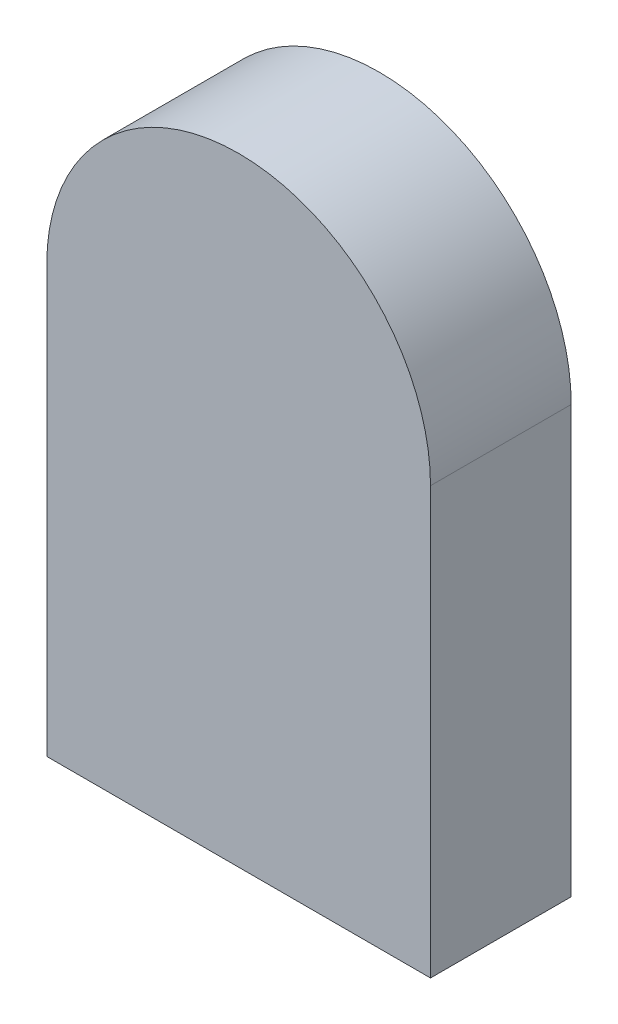
SolidWorks part; units mm, degrees
ref_plane "Front Plane" through (0, 0, 0) normal (0, 0, 1) x (1, 0, 0)
ref_plane "Top Plane" through (0, 0, 0) normal (0, 1, 0) x (1, 0, 0)
ref_plane "Right Plane" through (0, 0, 0) normal (1, 0, 0) x (0, 0, -1)
sketch "Sketch1" plane through (0, 0, 0) normal (0, 0, 1) x (1, 0, 0)
  line L0 (-11.43, -25.4) -> (11.43, -25.4)
  line L1 (-11.43, 0) -> (-11.43, -25.4)
  line L2 (11.43, 0) -> (11.43, -25.4)
  arc A0 (11.43, 0) -> (-11.43, 0) centre (0, 0) ccw
  point P6 (0, 0)
  point P7 (0, 0)
  dimension "D2" = 25.4
  dimension "D1" = 22.86
extrude "Boss-Extrude1" add sketch "Sketch1" along normal blind 8.382
